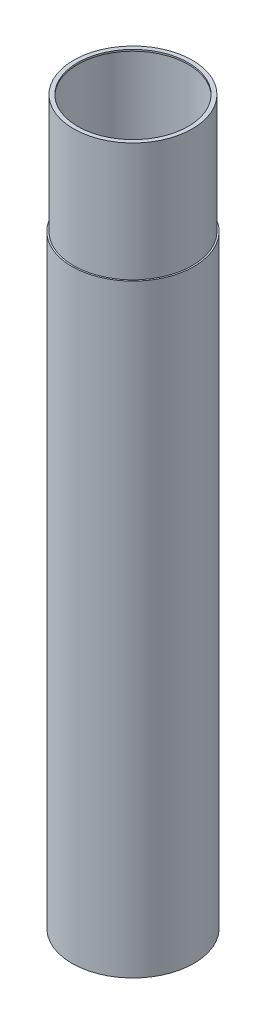
SolidWorks part; units mm, degrees
material "A-Glass Fiber"
ref_plane "Front Plane" through (0, 0, 0) normal (0, 0, 1) x (1, 0, 0)
ref_plane "Top Plane" through (0, 0, 0) normal (0, 1, 0) x (1, 0, 0)
ref_plane "Right Plane" through (0, 0, 0) normal (1, 0, 0) x (0, 0, -1)
sketch "Sketch1" plane through (0, 0, 0) normal (0, 0, 1) x (1, 0, 0)
  line L0 (78.16, 0) -> (78.16, 774)
  line L1 (76.2, 0) -> (76.2, 774)
  line L2 (78.16, 774) -> (76.2, 774)
  line L3 (76.2, 0) -> (78.16, 0)
  line L4 (0, 204.6154) -> (0, 85.8935) construction
  dimension "D1" = 76.2
  dimension "D2" = 774
  dimension "D3" = 1.96
revolve "Revolve1" add sketch "Sketch1" angle 360 about L4
sketch "Sketch3" plane through (0, 774, 0) normal (0, 1, 0) x (1, 0, 0)
  circle A2 centre (0, 0) radius 76.2 construction
  circle A3 centre (0, 0) radius 76.2
  circle A4 centre (0, 0) radius 75.2
  dimension "D1" = 1
extrude "Boss-Extrude1" add sketch "Sketch3" along normal blind 152 and the other way blind 152
sketch "Sketch4" plane through (0, 926, 0) normal (0, 1, 0) x (1, 0, 0)
  circle A0 centre (0, 0) radius 76.2
  circle A1 centre (0, 0) radius 70.915
extrude "Boss-Extrude2" add sketch "Sketch4" against normal blind 2
